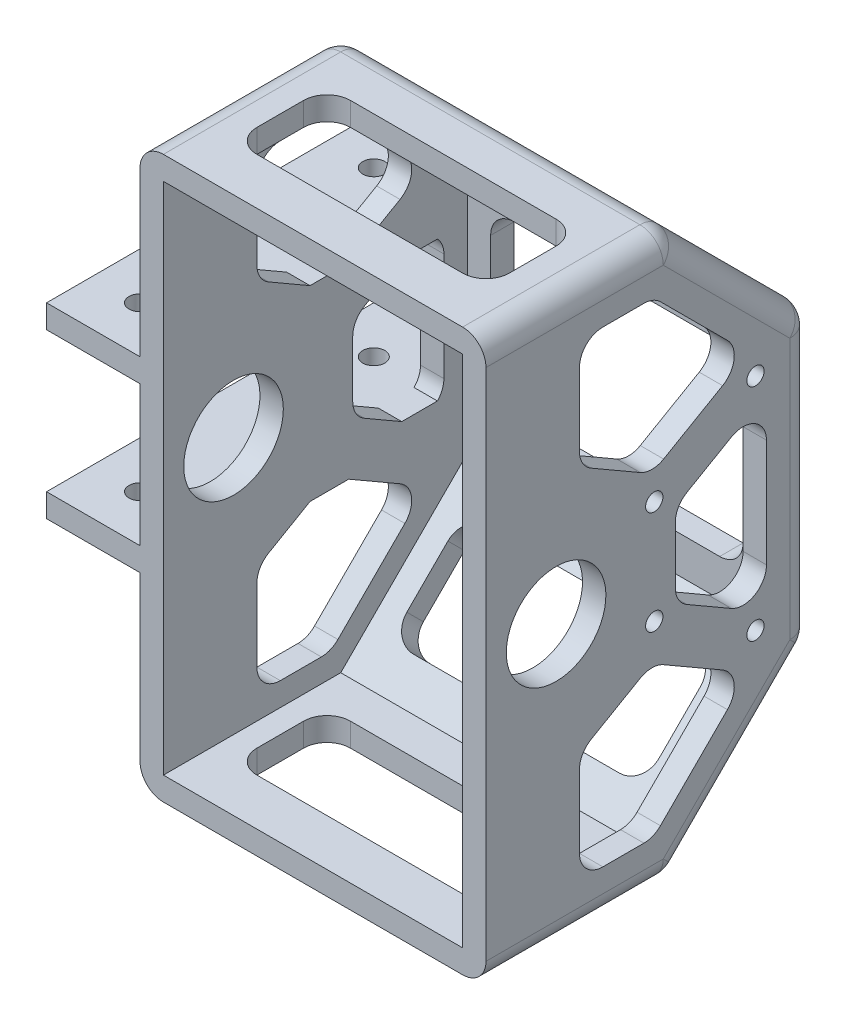
SolidWorks part; units mm, degrees
ref_plane "正面" through (0, 0, 0) normal (0, 0, 1) x (1, 0, 0)
ref_plane "平面" through (0, 0, 0) normal (0, 1, 0) x (1, 0, 0)
ref_plane "右側面" through (0, 0, 0) normal (1, 0, 0) x (0, 0, -1)
sketch "ｽｹｯﾁ1" plane through (0, 0, 0) normal (0, 0, 1) x (1, 0, 0)
  line L1 (-37, 60) -> (37, 60)
  line L2 (-37, 60) -> (-37, -60)
  line L3 (-37, -60) -> (37, -60)
  line L4 (37, 60) -> (37, -60)
  line L5 (-37, 60) -> (37, -60) construction
  line L6 (-37, -60) -> (37, 60) construction
  point P0 (0, 0)
  dimension "D1" = 120
  dimension "D2" = 74
extrude "ﾎﾞｽ - 押し出し1" add sketch "ｽｹｯﾁ1" along normal blind 70
chamfer "面取り2" distance 30 angle 45 2 edges at (0, 60, 0) (0, -60, 0)
sketch "ｽｹｯﾁ2" plane through (-37, 0, 0) normal (-1, 0, 0) x (0, 0, 1)
  line L0 (70, 60) -> (70, -60) construction
  line L1 (55, -23.6714) -> (55, -60)
  line L2 (55, 23.6714) -> (34.5, 11.8357)
  line L3 (34.5, 11.8357) -> (34.5, -11.8357)
  line L4 (34.5, -11.8357) -> (55, -23.6714)
  line L5 (55, -23.6714) -> (75.5, -11.8357)
  line L6 (75.5, -11.8357) -> (75.5, 11.8357)
  line L7 (75.5, 11.8357) -> (55, 23.6714)
  line L8 (70, -60) -> (30, -60) construction
  line L9 (34.5, -11.8357) -> (1.1122, -31.1122)
  line L10 (50, -23.6714) -> (50, -60)
  line L11 (0, -30) -> (30, -60) construction
  line L12 (55, 23.6714) -> (55, 60)
  line L13 (70, 60) -> (30, 60) construction
  line L14 (34.5, 11.8357) -> (1.1122, 31.1122)
  line L15 (30, 60) -> (0, 30) construction
  line L16 (32, -16.1658) -> (52.5, -28.0015)
  line L17 (32, -7.5056) -> (-1.3878, -26.782)
  line L18 (57.5, -28.0015) -> (80.5, -14.7224)
  line L19 (80.5, -14.7224) -> (80.5, 14.7224)
  line L20 (80.5, 14.7224) -> (57.5, 28.0015)
  line L21 (29.5, 11.8357) -> (29.5, -11.8357)
  line L22 (37, 16.1658) -> (3.6122, 35.4423)
  line L23 (52.5, 28.0015) -> (32, 16.1658)
  line L24 (60, 23.6714) -> (60, 60)
  line L25 (60, -23.6714) -> (60, -60)
  line L26 (37, -7.5056) -> (57.5, -19.3412)
  line L27 (37, -16.1658) -> (3.6122, -35.4423)
  line L28 (52.5, -19.3412) -> (70.5, -8.9489)
  line L29 (70.5, -8.9489) -> (70.5, 8.9489)
  line L30 (70.5, 8.9489) -> (52.5, 19.3412)
  line L31 (39.5, 11.8357) -> (39.5, -11.8357)
  line L32 (32, 7.5056) -> (-1.3878, 26.782)
  line L33 (57.5, 19.3412) -> (37, 7.5056)
  line L34 (50, 23.6714) -> (50, 60)
  line L47 (60, 50) -> (34.1421, 50)
  line L48 (34.1421, 50) -> (10, 25.8579)
  line L49 (10, 25.8579) -> (10, -25.8579)
  line L50 (10, -25.8579) -> (34.1421, -50)
  line L51 (34.1421, -50) -> (60, -50)
  line L52 (60, -50) -> (60, 50)
  line L53 (60, 50) -> (34.1421, 50)
  line L54 (34.1421, 50) -> (10, 25.8579)
  line L55 (10, 25.8579) -> (10, -25.8579)
  line L56 (10, -25.8579) -> (34.1421, -50)
  line L57 (34.1421, -50) -> (60, -50)
  line L58 (60, -50) -> (60, 50)
  circle A0 centre (55, 0) radius 10.65
  circle A1 centre (55, 0) radius 20.5 construction
  dimension "D1" = 21.3
  dimension "D2" = 15
  dimension "D3" = 41
  dimension "D4" = 5
  dimension "D5" = 5
  dimension "D6" = 10
shell "ｼｪﾙ1" thickness 5
extrude "ｶｯﾄ - 押し出し1" cut sketch "ｽｹｯﾁ2" against normal through all contours L56 L57 L10 L16 L27 | L32 L55 L17 L21 | L53 L54 L22 L23 L34 | L58 A0 | L58 A0
sketch "ｽｹｯﾁ3" plane through (0, -15, -15) normal (0, -0.7071, -0.7071) x (1, 0, 0)
  line L8 (-27, 53.6396) -> (-27, 31.2132)
  line L9 (-27, 31.2132) -> (27, 31.2132)
  line L10 (27, 31.2132) -> (27, 53.6396)
  line L11 (27, 53.6396) -> (-27, 53.6396)
  line L12 (-27, 53.6396) -> (-27, 31.2132)
  line L13 (-27, 31.2132) -> (27, 31.2132)
  line L14 (27, 31.2132) -> (27, 53.6396)
  line L15 (27, 53.6396) -> (-27, 53.6396)
  dimension "D1" = 10
extrude "ｶｯﾄ - 押し出し2" cut sketch "ｽｹｯﾁ3" against normal blind 70
sketch "ｽｹｯﾁ4" plane through (0, 15, -15) normal (0, 0.7071, -0.7071) x (1, 0, 0)
  line L8 (27, -53.6396) -> (27, -31.2132)
  line L9 (27, -31.2132) -> (-27, -31.2132)
  line L10 (-27, -31.2132) -> (-27, -53.6396)
  line L11 (-27, -53.6396) -> (27, -53.6396)
  line L12 (27, -53.6396) -> (27, -31.2132)
  line L13 (27, -31.2132) -> (-27, -31.2132)
  line L14 (-27, -31.2132) -> (-27, -53.6396)
  line L15 (-27, -53.6396) -> (27, -53.6396)
  dimension "D1" = 10
extrude "ｶｯﾄ - 押し出し3" cut sketch "ｽｹｯﾁ4" against normal blind 70
sketch "ｽｹｯﾁ5" plane through (0, 0, 0) normal (0, 0, -1) x (-1, 0, 0)
  line L8 (27, -20) -> (27, 20)
  line L9 (27, 20) -> (-27, 20)
  line L10 (-27, 20) -> (-27, -20)
  line L11 (-27, -20) -> (27, -20)
  line L12 (27, -20) -> (27, 20)
  line L13 (27, 20) -> (-27, 20)
  line L14 (-27, 20) -> (-27, -20)
  line L15 (-27, -20) -> (27, -20)
  dimension "D1" = 10
extrude "ｶｯﾄ - 押し出し4" cut sketch "ｽｹｯﾁ5" against normal blind 70
sketch "ｽｹｯﾁ7" plane through (0, 60, 0) normal (0, 1, 0) x (1, 0, 0)
  line L8 (27, -60) -> (27, -40)
  line L9 (27, -40) -> (-27, -40)
  line L10 (-27, -40) -> (-27, -60)
  line L11 (-27, -60) -> (27, -60)
  line L12 (27, -60) -> (27, -40)
  line L13 (27, -40) -> (-27, -40)
  line L14 (-27, -40) -> (-27, -60)
  line L15 (-27, -60) -> (27, -60)
  dimension "D1" = 10
extrude "ｶｯﾄ - 押し出し5" cut sketch "ｽｹｯﾁ7" against normal through all
fillet "ﾌｨﾚｯﾄ1" radius 5 62 edges at (27, 51.1612, 24.6967) (-27, 51.1612, 24.6967) (-27, 35.3033, 8.8388) (27, 35.3033, 8.8388) (-27, 20, 2.5) (-27, -20, 2.5) (27, 20, 2.5) (27, -20, 2.5) (-27, -35.3033, 8.8388) (-27, -51.1612, 24.6967) (27, -51.1612, 24.6967) (27, -35.3033, 8.8388) (34.5, -50, 34.1421) (34.5, -29.596, 13.7382) (34.5, -17.6092, 34.5) (34.5, -26.5581, 50) (34.5, -50, 50) (34.5, 26.5581, 50) (34.5, 17.6092, 34.5) (34.5, 29.596, 13.7382) (34.5, 50, 34.1421) (34.5, 50, 50) (34.5, -20.2073, 10) (34.5, -8.9489, 29.5) (34.5, 8.9489, 29.5) (34.5, 20.2073, 10) (-34.5, 29.596, 13.7382) (-34.5, 50, 34.1421) (-34.5, 50, 50) (-34.5, 26.5581, 50) (-34.5, 17.6092, 34.5) (-34.5, 20.2073, 10) (-34.5, 8.9489, 29.5) (-34.5, -20.2073, 10) (-34.5, -8.9489, 29.5) (-34.5, -29.596, 13.7382) (-34.5, -17.6092, 34.5) (-34.5, -26.5581, 50) (-34.5, -50, 50) (-34.5, -50, 34.1421) (-27, -57.5, 60) (-27, -57.5, 40) (27, -57.5, 40) (27, -57.5, 60) (27, 57.5, 60) (27, 57.5, 40) (-27, 57.5, 40) (-27, 57.5, 60) (37, -45, 15) (37, -60, 50) (-37, -60, 50) (-37, -45, 15) (0, -30, 0) (-37, 0, 0) (-37, 45, 15) (0, 60, 30) (-37, 60, 50) (37, 60, 50) (0, 30, 0) (37, 45, 15) (37, 0, 0) (0, -60, 30)
sketch "ｽｹｯﾁ10" plane through (-37, 0, 0) normal (-1, 0, 0) x (0, 0, 1)
  line L0 (5, 27.9289) -> (5, -27.9289) construction
  line L1 (70, 17.5) -> (5, 17.5)
  line L2 (70, 17.5) -> (70, -17.5)
  line L3 (70, -17.5) -> (5, -17.5)
  line L4 (5, 17.5) -> (5, -17.5)
  line L5 (70, 17.5) -> (5, -17.5) construction
  line L6 (70, -17.5) -> (5, 17.5) construction
  line L7 (70, 55) -> (70, -55) construction
  line L8 (70, -15) -> (5, -15)
  line L9 (70, 20) -> (5, 20)
  line L10 (70, -20) -> (5, -20)
  line L11 (70, 15) -> (5, 15)
  line L13 (5, -15) -> (0, -15)
  line L14 (5, -15) -> (5, -20)
  line L15 (5, -20) -> (0, -20)
  line L16 (0, -15) -> (0, -20)
  line L17 (2.5, -20) -> (2.5, -15) construction
  line L18 (5, -17.5) -> (0, -17.5) construction
  line L19 (5, 20) -> (0, 20)
  line L20 (5, 20) -> (5, 15)
  line L21 (5, 15) -> (0, 15)
  line L22 (0, 20) -> (0, 15)
  line L23 (2.5, 15) -> (2.5, 20) construction
  line L24 (5, 17.5) -> (0, 17.5) construction
  circle A0 centre (55, 0) radius 10.65 construction
  point P0 (37.5, 0)
  point P110 (2.5, -17.5)
  point P114 (2.5, 17.5)
  line M12 (47.5, 25.1147) -> (37, 19.0526)
  arc M13 (37, 19.0526) -> (32, 19.0526) centre (34.5, 23.3827) cw
  line M14 (32, 19.0526) -> (19.3813, 26.338)
  arc M17 (10, 11.547) -> (17.5, 15.8771) centre (15, 11.547) cw
  line M18 (17.5, 15.8771) -> (27, 10.3923)
  line M22 (27, -10.3923) -> (17.5, -15.8771)
  arc M23 (17.5, -15.8771) -> (10, -11.547) centre (15, -11.547) cw
  line M28 (19.3813, -26.338) -> (32, -19.0526)
  arc M29 (32, -19.0526) -> (37, -19.0526) centre (34.5, -23.3827) cw
  line M30 (37, -19.0526) -> (47.5, -25.1147)
  line M36 (70, -55) -> (70, 55)
  line M39 (5, 27.9289) -> (5, -27.9289)
  dimension "D1" = 0
  dimension "D2" = 35
  dimension "D3" = 0
  dimension "D4" = 2.5
  dimension "D5" = 2.5
extrude "ﾎﾞｽ - 押し出し3" add sketch "ｽｹｯﾁ10" along normal blind 20 and the other way blind 5 contours L8 L4 L3 M36 M22 M23 | L10 L3 M36 M39 M28 M29 M30 | L11 L1 M36 M39 M17 M18 | L9 L1 M36 M12 M13 M14 M39 | L10 M30 M29 M28 | L9 M12 M14 M13 | L8 M22 M23 | L11 M18 M17 | L19 L22 L21 M39 | L13 L16 L15 L4 M39
sketch "ｽｹｯﾁ12" plane through (0, -20, 0) normal (0, -1, 0) x (1, 0, 0)
  line L0 (-57, 70) -> (-57, 0) construction
  line L1 (-37, 70) -> (-57, 70) construction
  line L2 (-57, 70) -> (-57, 0) construction
  circle A0 centre (-47, 60) radius 2.35
  circle A1 centre (-47, 10) radius 2.35
  dimension "D1" = 10
  dimension "D2" = 10
  dimension "D3" = 4.7
  dimension "D4" = 50
  dimension "D5" = 4.7
  dimension "D6" = 10
extrude "ｶｯﾄ - 押し出し7" cut sketch "ｽｹｯﾁ12" against normal through all
sketch "ｽｹｯﾁ13" plane through (37, 0, 0) normal (1, 0, 0) x (0, 0, -1)
  line L0 (-34, -10.0111) -> (-12.3494, -22.5111) construction
  line L1 (-34, -10.0111) -> (-34, 12.1244) construction
  line L2 (-34, 12.1244) -> (-12.3494, 24.6244) construction
  line L3 (-12.3494, 24.6244) -> (-12.3494, -22.5111) construction
  circle A0 centre (-12.3494, 24.6244) radius 1.85
  circle A1 centre (-34, 12.1244) radius 1.85
  circle A2 centre (-34, -10.0111) radius 1.85
  circle A3 centre (-12.3494, -22.5111) radius 1.85
  dimension "D1" = 3.7
  dimension "D2" = 3.7
  dimension "D3" = 3.7
  dimension "D4" = 3.7
extrude "ｶｯﾄ - 押し出し8" cut sketch "ｽｹｯﾁ13" against normal blind 10
